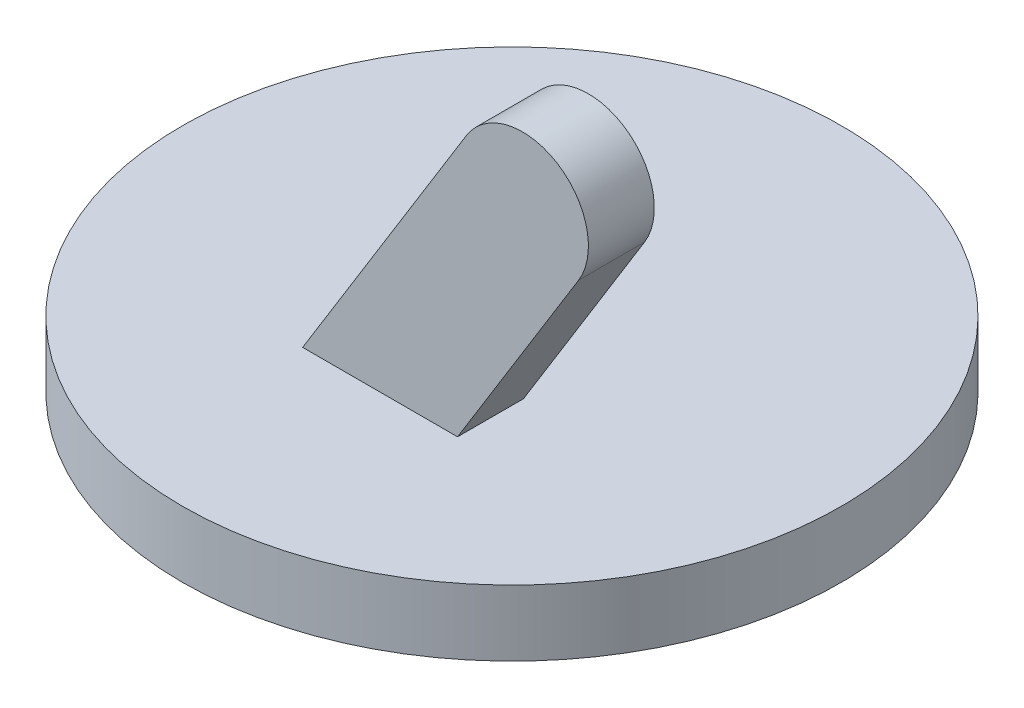
SolidWorks part; units mm, degrees
ref_plane "前视基准面" through (0, 0, 0) normal (0, 0, 1) x (1, 0, 0)
ref_plane "上视基准面" through (0, 0, 0) normal (0, 1, 0) x (1, 0, 0)
ref_plane "右视基准面" through (0, 0, 0) normal (1, 0, 0) x (0, 0, -1)
other "Configuration Table"
sketch "草图1" plane through (0, 0, 0) normal (0, 1, 0) x (1, 0, 0)
  circle A0 centre (0, 0) radius 25
  dimension "D1" = 50
extrude "凸台-拉伸1" add sketch "草图1" along normal blind 5
ref_plane "基准面1" through (0, 0, 5) normal (0, 0, 1) x (1, 0, 0)
sketch "草图2" plane through (0, 0, 5) normal (0, 0, 1) x (1, 0, 0)
  line L0 (5.8755, 5) -> (15.0549, 19.8741)
  line L1 (25, 5) -> (-25, 5) construction
  line L2 (6.5451, 25.1259) -> (-5.8755, 5)
  line L3 (10.8, 22.5) -> (0, 5) construction
  line L4 (-5.8755, 5) -> (5.8755, 5)
  arc A0 (15.0549, 19.8741) -> (6.5451, 25.1259) centre (10.8, 22.5) ccw
  dimension "D1" = 5
  dimension "D2" = 180
  dimension "D3" = 17.5
  dimension "D4" = 10.8
extrude "凸台-拉伸2" add sketch "草图2" along normal blind 5
